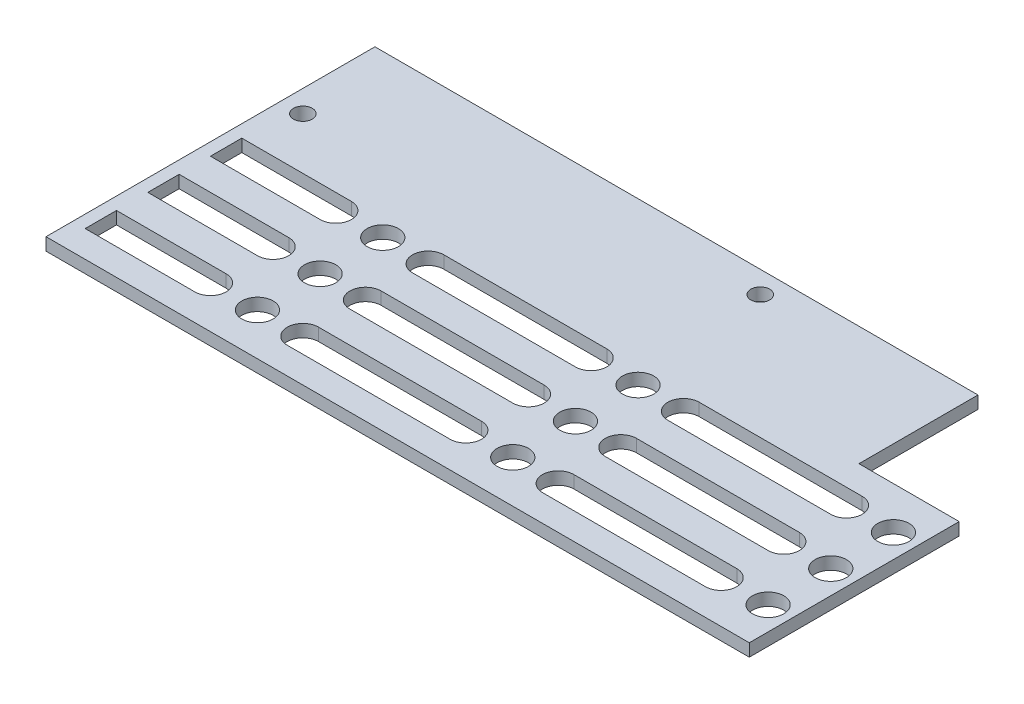
SolidWorks part; units mm, degrees
ref_plane "Front Plane" through (0, 0, 0) normal (0, 0, 1) x (1, 0, 0)
ref_plane "Top Plane" through (0, 0, 0) normal (0, 1, 0) x (1, 0, 0)
ref_plane "Right Plane" through (0, 0, 0) normal (1, 0, 0) x (0, 0, -1)
sketch "Sketch1" plane through (0, 0, 0) normal (0, 1, 0) x (1, 0, 0)
  line L1 (-112.25, 0) -> (0, 0)
  line L2 (-112.25, 0) -> (-112.25, 52.5)
  line L3 (-112.25, 52.5) -> (-16, 52.5)
  line L4 (0, 0) -> (0, 33.5)
  line L7 (0, 33.5) -> (-16, 33.5)
  line L8 (-16, 52.5) -> (-16, 33.5)
  circle A0 centre (-47.25, 49) radius 1.5
  circle A1 centre (-108.75, 37.5) radius 1.5
  dimension "D2" = 3
  dimension "D1" = 112.25
  dimension "D3" = 3.5
  dimension "D4" = 3.5
  dimension "D5" = 61.5
  dimension "D6" = 11.5
  dimension "D7" = 49
  dimension "D8" = 15.5
  dimension "D9" = 16
extrude "Boss-Extrude1" add sketch "Sketch1" along normal blind 2
sketch "Sketch2" plane through (0, 0, 0) normal (0, -1, 0) x (-1, 0, 0)
  circle A0 centre (108.75, 37.5) radius 2.5
  circle A1 centre (108.75, 37.5) radius 1.5
  circle A2 centre (108.75, 37.5) radius 1.5 construction
  dimension "D1" = 5
extrude "Boss-Extrude2" add sketch "Sketch2" along normal blind 3
sketch "Sketch3" plane through (0, 2, 0) normal (0, 1, 0) x (1, 0, 0)
  line L0 (-37.25, 26.75) -> (-11.25, 26.75) construction
  line L1 (-37.25, 29.25) -> (-11.25, 29.25)
  line L2 (-37.25, 24.25) -> (-11.25, 24.25)
  line L3 (0, 0) -> (0, 33.5) construction
  line L4 (0, 33.5) -> (-16, 33.5) construction
  arc A0 (-37.25, 29.25) -> (-37.25, 24.25) centre (-37.25, 26.75) ccw
  arc A1 (-11.25, 24.25) -> (-11.25, 29.25) centre (-11.25, 26.75) ccw
  circle A2 centre (-3.75, 26.75) radius 2.5
  point P2 (-24.25, 26.75)
  point P9 (-47.7579, 23.3188)
  point P10 (0, 0)
  point P11 (0, 0)
  point P12 (-7.3662, 24.0722)
  point P13 (-18.9607, 24.9898)
  dimension "D1" = 26
  dimension "D2" = 5
  dimension "D3" = 7.5
  dimension "D4" = 3.75
  dimension "D5" = 6.75
extrude "Cut-Extrude1" cut sketch "Sketch3" against normal up to next
pattern_linear "LPattern1" count 3 spacing 40.75 along (-1, 0, 0) count 3 spacing 10 along (0, 0, 1) of "Cut-Extrude1"
sketch "Sketch4" plane through (0, 2, 0) normal (0, 1, 0) x (1, 0, 0)
  line L0 (-92.75, 29.25) -> (-112.25, 29.25) construction
  line L1 (-112.25, 0) -> (-110.25, 0)
  line L2 (-112.25, 0) -> (-112.25, 29.25)
  line L3 (-112.25, 29.25) -> (-110.25, 29.25)
  line L4 (-110.25, 0) -> (-110.25, 29.25)
  dimension "D1" = 2
extrude "Boss-Extrude3" add sketch "Sketch4" against normal up to surface (2 mm away) up to face at (-44.5, 0, -29.25)
equation "\"D3@Sketch3\"=\"D2@Sketch3\"*1.5"
equation "\"D4@Sketch3\"=\"D3@Sketch3\"/2"
